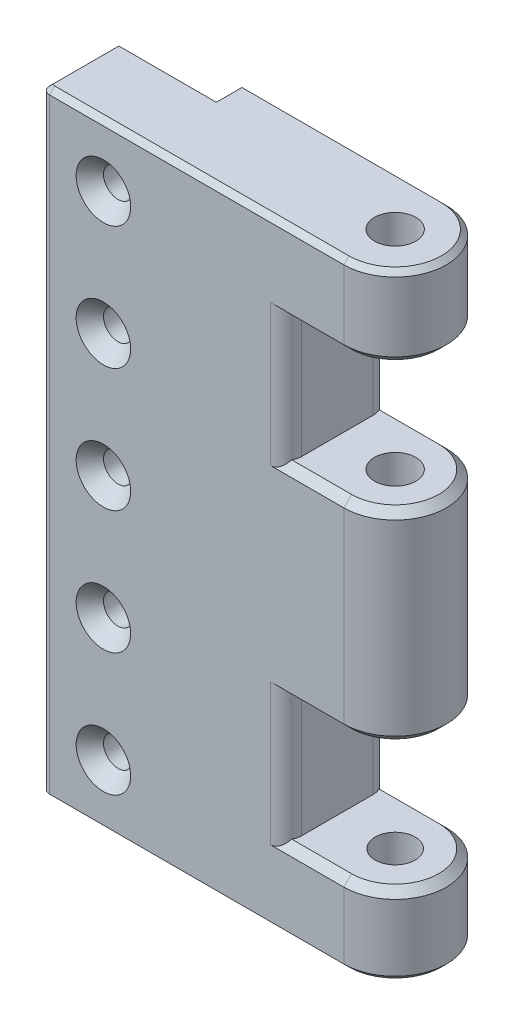
SolidWorks part; units mm, degrees
material "ASA"
ref_plane "Front Plane" through (0, 0, 0) normal (0, 0, 1) x (1, 0, 0)
ref_plane "Top Plane" through (0, 0, 0) normal (0, 1, 0) x (1, 0, 0)
ref_plane "Right Plane" through (0, 0, 0) normal (1, 0, 0) x (0, 0, -1)
sketch "Sketch1" plane through (0, 0, 0) normal (0, 1, 0) x (1, 0, 0)
  line L0 (-15.875, -4.7625) -> (-15.875, -15.875)
  line L1 (-15.875, -15.875) -> (30.8356, -15.875)
  line L2 (30.8356, 0) -> (0, 0)
  line L3 (0, 0) -> (0, -4.7625)
  line L4 (0, -4.7625) -> (-15.875, -4.7625)
  arc A0 (30.8356, -15.875) -> (30.8356, 0) centre (30.8356, -7.9375) ccw
  dimension "D2" = 7.9375
  dimension "D1" = 15.875
  dimension "D3" = 3.175
  dimension "D4" = 4.7625
  dimension "D5" = 38.7731
extrude "Boss-Extrude1" add sketch "Sketch1" along normal blind 95.25
sketch "Sketch4" plane through (0, 0, 15.875) normal (0, 0, 1) x (1, 0, 0)
  line L0 (0, 85.725) -> (-12.7, 85.725) construction
  line L2 (0, 95.25) -> (0, 0) construction
  line L3 (-15.875, 95.25) -> (-15.875, 0) construction
  line L5 (-15.875, 47.625) -> (30.8356, 47.625) construction
  line L6 (30.8356, 95.25) -> (30.8356, 0) construction
  point P0 (-6.35, 85.725)
  point P13 (-6.35, 66.675)
  point P14 (-6.35, 47.625)
  point P15 (-6.35, 28.575)
  point P16 (-6.35, 9.525)
  dimension "D1" = 12.7
  dimension "D3" = 19.05
  dimension "D2" = 5
hole_wizard "CSK for #8 Flat Head Machine Screw1" positions "Sketch4" profile "Sketch5" countersink size "#8" standard "ANSI Inch" end condition through all
sketch "Sketch5" plane through (-6.35, 85.725, 15.875) normal (1, 0, 0) x (0, -1, 0)
  line L0 (0, 0) -> (0, 15.875)
  line L1 (0, 15.875) -> (2.2479, 15.875)
  line L2 (2.2479, 15.875) -> (2.2479, 2.2645)
  line L3 (2.2479, 2.2645) -> (4.2164, 0)
  line L5 (4.2164, 0) -> (0, 0)
  line L6 (-2.2479, 2.2645) -> (-4.2164, 0) construction
  line L11 (0, -6.35) -> (0, 107.95) construction
  dimension "Thru Hole Dia." = 4.4958
  dimension "Thru Hole Depth" = 15.875
  dimension "Near C'Sink Dia." = 8.4328
  dimension "Near C'Sink Angle" = 82
sketch "Sketch2" plane through (0, 95.25, 0) normal (0, 1, 0) x (1, 0, 0)
  circle A0 centre (30.8356, -7.9375) radius 2.9464
  arc A1 (30.8356, -15.875) -> (30.8356, 0) centre (30.8356, -7.9375) ccw construction
  dimension "D1" = 5.8928
extrude "Cut-Extrude1" cut sketch "Sketch2" against normal through all
other "Move Face1" face at (30.8356, 0, 10.8839) parameters "D1"=0.25
sketch "Sketch6" plane through (0, 0, 15.875) normal (0, 0, 1) x (1, 0, 0)
  line L0 (38.7731, 0) -> (38.7731, 95.25) construction
  line L1 (22.8981, 82.55) -> (38.7731, 82.55)
  line L2 (22.8981, 82.55) -> (22.8981, 63.5)
  line L3 (22.8981, 63.5) -> (38.7731, 63.5)
  line L4 (38.7731, 82.55) -> (38.7731, 63.5)
  line L5 (22.8981, 31.75) -> (38.7731, 31.75)
  line L6 (22.8981, 31.75) -> (22.8981, 12.7)
  line L7 (22.8981, 12.7) -> (38.7731, 12.7)
  line L8 (38.7731, 31.75) -> (38.7731, 12.7)
  line L10 (30.8356, 60.2185) -> (30.8356, 86.5414) construction
  line L11 (27.6392, 95.25) -> (27.6392, 0) construction
  line L12 (34.032, 0) -> (34.032, 95.25) construction
  line L15 (38.7731, 82.55) -> (38.7731, 95.25) construction
  line L16 (38.7731, 12.7) -> (38.7731, 0) construction
  line L17 (34.032, 95.25) -> (27.6392, 95.25) construction
  line L18 (27.6392, 0) -> (34.032, 0) construction
  line L19 (38.7731, 95.25) -> (30.8356, 95.25) construction
  dimension "D1" = 31.75
  dimension "D2" = 12.7
  dimension "D3" = 19.05
extrude "Cut-Extrude2" cut sketch "Sketch6" against normal through all
other "Move Face2" face at (30.8356, 12.7, 4.7411) face at (30.8356, 63.5, 4.7411) parameters "D1"=0.4
other "Move Face3" face at (22.8981, 72.825, 7.9375) face at (22.8981, 22.025, 7.9375) parameters "D1"=1
other "Move Face4" face at (30.8356, 12.3, 4.7411) parameters "D1"=0.1
fillet "Fillet1" radius 1.2 1 edges at (-15.875, 47.625, 15.875)
fillet "Fillet2" radius 2.4 4 edges at (21.8981, 22.025, 0) (21.8981, 72.825, 0) (21.8981, 22.025, 15.875) (21.8981, 72.825, 15.875)
chamfer "Chamfer1" distance 0.8 angle 45 10 edges at (-15.875, 0, 9.7188) (-15.5235, 0, 15.5235) (8.0803, 0, 15.875) (15.4178, 0, 0) (38.7731, 0, 7.9375) (-15.875, 95.25, 9.7188) (-15.5235, 95.25, 15.5235) (8.0803, 95.25, 15.875) (15.4178, 95.25, 0) (38.7731, 95.25, 7.9375)
chamfer "Chamfer2" distance 1.2 angle 45 12 edges at (25.1668, 12.3, 0) (25.1668, 12.3, 15.875) (38.7731, 12.3, 7.9375) (25.1668, 31.75, 15.875) (25.1668, 31.75, 0) (38.7731, 31.75, 7.9375) (25.1668, 63.1, 0) (25.1668, 63.1, 15.875) (38.7731, 63.1, 7.9375) (25.1668, 82.55, 15.875) (25.1668, 82.55, 0) (38.7731, 82.55, 7.9375)
mirror "Mirror1" about plane through (0, 0, 0) normal (1, 0, 0) of bodies 109 108
sketch "Sketch7" plane through (0, 0, 0) normal (0, 0, -1) x (-1, 0, 0)
  line L0 (-30.8356, 38.1) -> (-18.1356, 38.1) construction
  line L1 (-30.8356, 61.9) -> (-30.8356, 32.95) construction
  line L2 (-21.5766, 31.75) -> (-30.8356, 31.75) construction
  line L3 (18.1356, 38.1) -> (30.8356, 38.1) construction
  line L5 (30.8356, 61.9) -> (30.8356, 32.95) construction
  text T0 "R" font "Segoe UI" height 9.525
  text T1 "L" font "Segoe UI" height 9.525
  dimension "D1" = 12.7
  dimension "D2" = 6.35
extrude "Cut-Extrude3" cut sketch "Sketch7" against normal blind 0.8
delete or keep bodies "Body-Delete/Keep 1" type keep bodies bodies 108
delete or keep bodies "Body-Delete/Keep 2" [suppressed] type keep bodies bodies 111
equation "\"D1@Move Face1\"= 0.25mm"
equation "\"D1@Move Face2\"= 0.4mm"
equation "\"D1@Move Face3\"= 1mm"
equation "\"D1@Fillet1\"=1.2mm"
equation "\"D1@Fillet2\"=2.4mm"
equation "\"D1@Chamfer1\"=0.8mm"
equation "\"D1@Chamfer2\"=1.2mm"
equation "\"D1@Cut-Extrude3\"=0.8mm"
equation "\"D1@Move Face4\"= 0.1mm"
